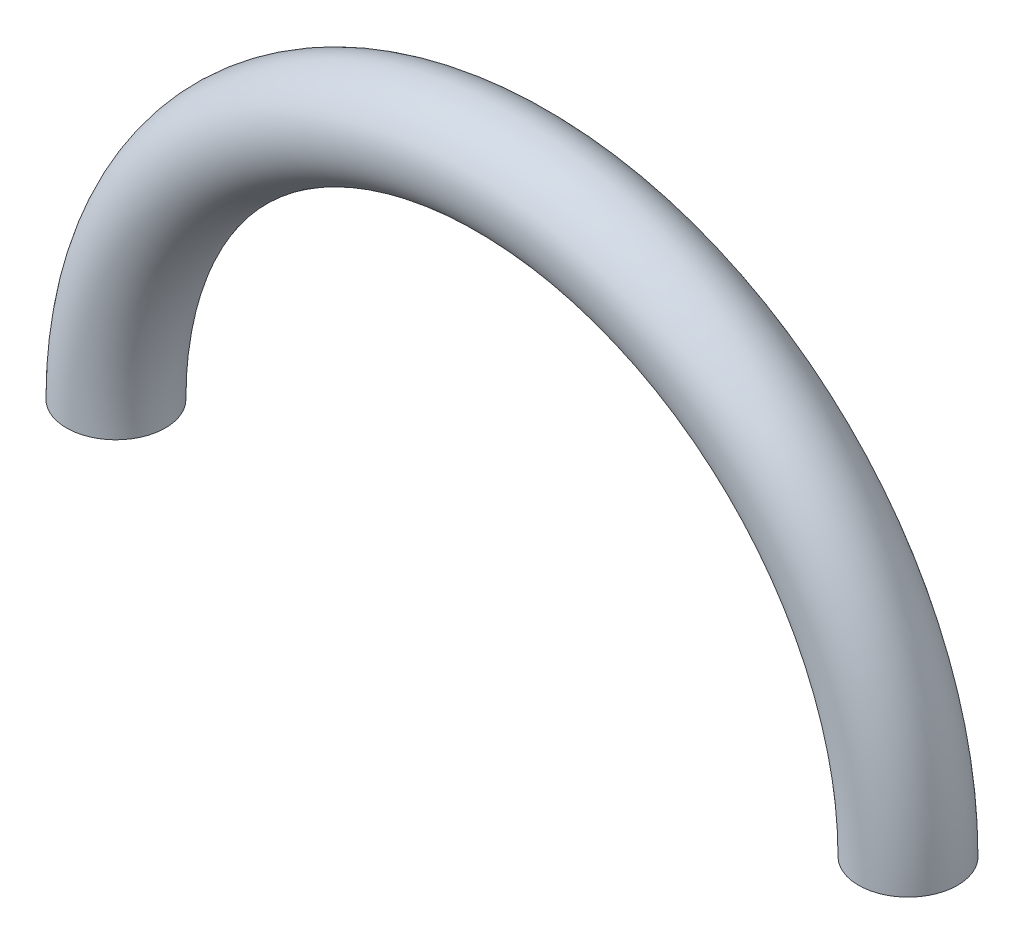
SolidWorks part; units mm, degrees
material "PMMA"
ref_plane "Front Plane" through (0, 0, 0) normal (0, 0, 1) x (1, 0, 0)
ref_plane "Top Plane" through (0, 0, 0) normal (0, 1, 0) x (1, 0, 0)
ref_plane "Right Plane" through (0, 0, 0) normal (1, 0, 0) x (0, 0, -1)
sketch "Sketch1" plane through (0, 0, 0) normal (0, 1, 0) x (1, 0, 0)
  line L0 (0, 0) -> (0, 2.4496) construction
  circle A0 centre (127, 0) radius 12.7
  circle A1 centre (127, 0) radius 15.875
  dimension "D1" = 31.75
  dimension "D2" = 25.4
  dimension "D3" = 127
revolve "Revolve1" add sketch "Sketch1" angle 180 about L0
sketch "Sketch2" plane through (0, 0, 0) normal (0, -1, 0) x (1, 0, 0)
  line L0 (0, 0) -> (0, 57.0053) construction
  circle A3 centre (127, 0) radius 12.69
  dimension "D1" = 25.38
  dimension "D2" = 127
revolve "Revolve2" add sketch "Sketch2" angle 180 about L0
